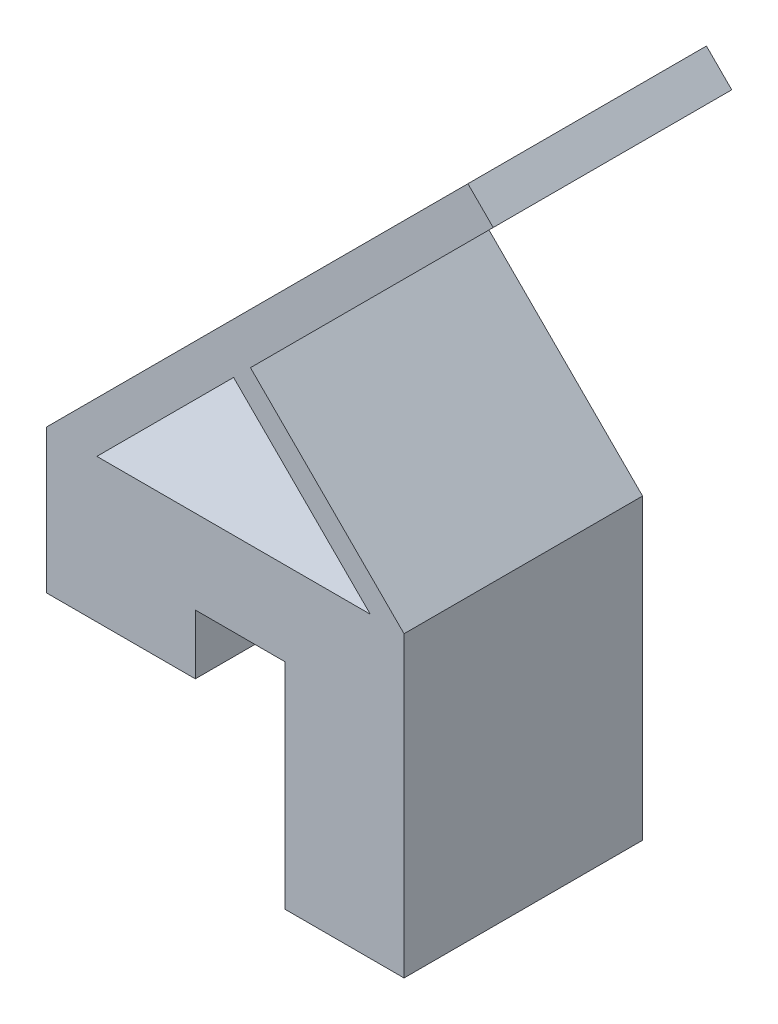
SolidWorks part; units mm, degrees
ref_plane "Front Plane" through (0, 0, 0) normal (0, 0, 1) x (1, 0, 0)
ref_plane "Top Plane" through (0, 0, 0) normal (0, 1, 0) x (1, 0, 0)
ref_plane "Right Plane" through (0, 0, 0) normal (1, 0, 0) x (0, 0, -1)
sketch "Sketch1" plane through (0, 0, 0) normal (0, 0, 1) x (1, 0, 0)
  line L1 (5.2252, 15.5405) -> (15.2252, 15.5405)
  line L2 (5.2252, 8.5135) -> (5.2252, -9.4595)
  line L3 (5.2252, -9.4595) -> (15.2252, -9.4595)
  line L4 (15.2252, 15.5405) -> (15.2252, -9.4595)
  line L5 (5.2252, 15.5405) -> (-14.7748, 15.5405)
  line L6 (5.2252, 8.5135) -> (5.2252, 3.5135)
  line L7 (-2.2748, 3.5135) -> (-14.7748, 3.5135)
  line L8 (-14.7748, 15.5405) -> (-14.7748, 3.5135)
  line L10 (5.2252, 3.5135) -> (5.2252, 8.5135)
  line L11 (5.2252, 8.5135) -> (-2.2748, 8.5135)
  line L12 (-2.2748, 3.5135) -> (-2.2748, 8.5135)
  dimension "D1" = 10
  dimension "D2" = 25
  dimension "D3" = 7.5
  dimension "D4" = 5
  dimension "D5" = 20
extrude "Boss-Extrude2" add sketch "Sketch1" along normal blind 20 contours L7 L12 L11 L2 L3 L4 L1 L5 L8
sketch "Sketch2" plane through (0, 0, 20) normal (0, 0, 1) x (1, 0, 0)
  line L0 (-14.7748, 15.5405) -> (20.5806, 50.8959)
  line L1 (20.5806, 50.8959) -> (22.7019, 48.7746)
  line L2 (22.7019, 48.7746) -> (2.3465, 28.4192)
  line L3 (-14.7748, 15.5405) -> (15.2252, 15.5405) construction
  line L4 (-10.5321, 15.5405) -> (-14.7748, 15.5405)
  line L5 (15.2252, 15.5405) -> (2.3465, 28.4192)
  line L7 (0.9323, 27.005) -> (12.3968, 15.5405)
  line L8 (12.3968, 15.5405) -> (15.2252, 15.5405)
  line L9 (0.9323, 27.005) -> (-10.5321, 15.5405)
  dimension "D1" = 3
  dimension "D2" = 50
  dimension "D3" = 18.2132
  dimension "D4" = 2
extrude "Boss-Extrude3" add sketch "Sketch2" against normal blind 20
